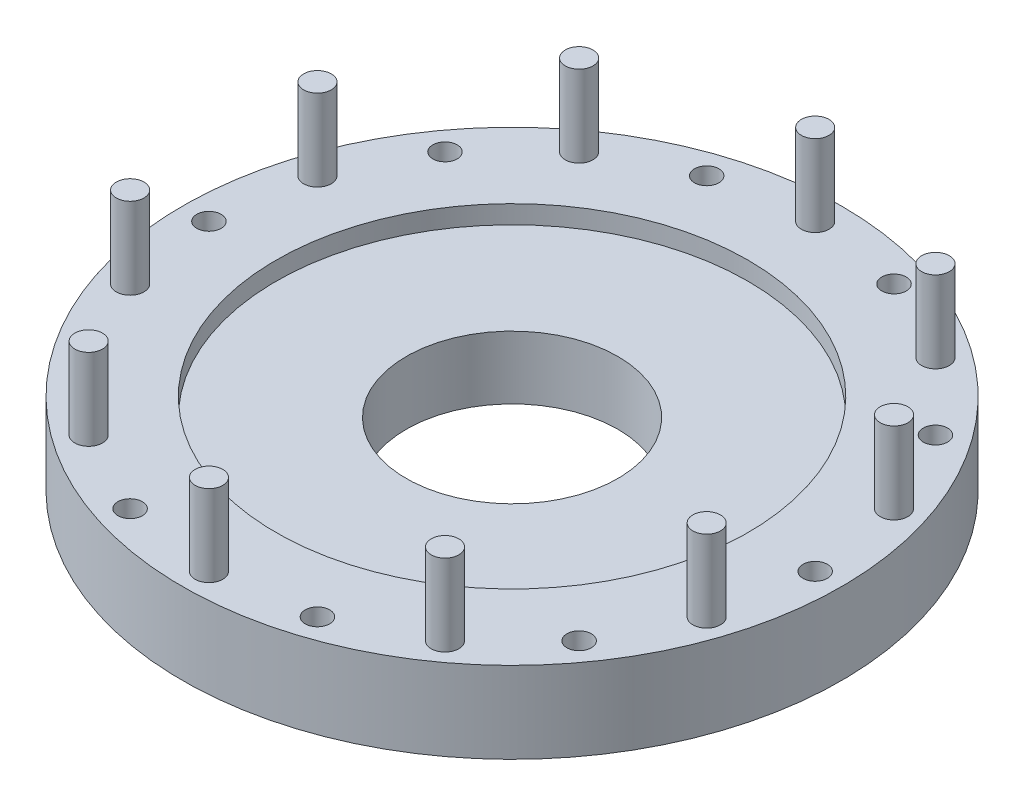
SolidWorks part; units mm, degrees
material "ABS"
ref_plane "Front Plane" through (0, 0, 0) normal (0, 0, 1) x (1, 0, 0)
ref_plane "Top Plane" through (0, 0, 0) normal (0, 1, 0) x (1, 0, 0)
ref_plane "Right Plane" through (0, 0, 0) normal (1, 0, 0) x (0, 0, -1)
sketch "Sketch1" plane through (0, 0, 0) normal (0, 0, 1) x (1, 0, 0)
  line L0 (0, -1.7519) -> (0, 48.3018) construction
  line L1 (-29, 10) -> (-40.5, 10)
  line L4 (-40.5, 10) -> (-40.5, 0)
  line L5 (-40.5, 0) -> (-13, 0)
  line L6 (-13, 0) -> (-13, 7.75)
  line L7 (-13, 7.75) -> (-29, 7.75)
  line L8 (-29, 7.75) -> (-29, 10)
  dimension "D1" = 40.5
  dimension "D3" = 2.25
  dimension "D2" = 29
  dimension "D4" = 13
  dimension "D5" = 10
revolve "Revolve1" add sketch "Sketch1" angle 360 about L0
sketch "Sketch2" plane through (0, 10, 0) normal (0, 1, 0) x (1, 0, 0)
  line L0 (0, 37.25) -> (0, 0) construction
  line L1 (0, 0) -> (11.5109, 35.4269) construction
  circle A0 centre (0, 0) radius 37.25 construction
  circle A1 centre (0, 37.25) radius 1.7
  circle A2 centre (11.5109, 35.4269) radius 1.5
  circle A3 centre (21.895, 30.1359) radius 1.7
  circle A4 centre (30.1359, 21.895) radius 1.5
  circle A5 centre (35.4269, 11.5109) radius 1.7
  circle A6 centre (37.25, 0) radius 1.5
  circle A7 centre (35.4269, -11.5109) radius 1.7
  circle A8 centre (30.1359, -21.895) radius 1.5
  circle A9 centre (21.895, -30.1359) radius 1.7
  circle A10 centre (11.5109, -35.4269) radius 1.5
  circle A11 centre (0, -37.25) radius 1.7
  circle A12 centre (-11.5109, -35.4269) radius 1.5
  circle A13 centre (-21.895, -30.1359) radius 1.7
  circle A14 centre (-30.1359, -21.895) radius 1.5
  circle A15 centre (-35.4269, -11.5109) radius 1.7
  circle A16 centre (-37.25, 0) radius 1.5
  circle A17 centre (-35.4269, 11.5109) radius 1.7
  circle A18 centre (-30.1359, 21.895) radius 1.5
  circle A19 centre (-21.895, 30.1359) radius 1.7
  circle A20 centre (-11.5109, 35.4269) radius 1.5
  point P37 (0, 0)
  dimension "D5" = 10
  dimension "D1" = 74.5
  dimension "D2" = 3.4
  dimension "D3" = 3
  dimension "D4" = 18
extrude "Cut-Extrude1" cut sketch "Sketch2" against normal through all both and the other way through all
sketch "Sketch3" plane through (0, 0, 0) normal (0, 0, 1) x (1, 0, 0)
  line L0 (28.5, 4) -> (28.5, 0)
  line L2 (28.5, 0) -> (21.5, 0)
  line L3 (21.5, 0) -> (21.5, 4)
  line L6 (25, 4) -> (25, 0) construction
  line L7 (0, -19.0654) -> (0, 22.7714) construction
  line L8 (-40.5, 0) -> (40.5, 0) construction
  line L9 (28.5, 4) -> (21.5, 4)
  dimension "D1" = 25
  dimension "D2" = 4
  dimension "D3" = 7
revolve "Cut-Revolve1" cut sketch "Sketch3" angle 360 about L7
sketch "Sketch4" plane through (0, 0, 0) normal (0, -1, 0) x (1, 0, 0)
  line L0 (10.8507, 38.5329) -> (8.4909, 36.4081)
  line L1 (8.4909, 36.4081) -> (9.1511, 33.3021)
  line L2 (9.1511, 33.3021) -> (12.1711, 32.3208)
  line L3 (12.1711, 32.3208) -> (14.5309, 34.4456)
  line L4 (14.5309, 34.4456) -> (13.8707, 37.5516)
  line L5 (13.8707, 37.5516) -> (10.8507, 38.5329)
  line L6 (13.8707, 37.5516) -> (9.1511, 33.3021) construction
  line L49 (33.2939, 22.2269) -> (31.4274, 24.7959)
  line L50 (12.3607, 38.0423) -> (12.5152, 38.5178) construction
  line L51 (16.0251, 37.3773) -> (16.3077, 37.2855) construction
  line L52 (31.4274, 24.7959) -> (28.2694, 24.464)
  line L53 (28.2694, 24.464) -> (26.9779, 21.5631)
  line L54 (26.9779, 21.5631) -> (28.8443, 18.9941)
  line L55 (28.8443, 18.9941) -> (32.0024, 19.326)
  line L56 (32.0024, 19.326) -> (33.2939, 22.2269)
  line L57 (40, -1.5877) -> (40, 1.5877)
  line L58 (40, 1.5877) -> (37.25, 3.1754)
  line L59 (37.25, 3.1754) -> (34.5, 1.5877)
  line L60 (34.5, 1.5877) -> (34.5, -1.5877)
  line L61 (34.5, -1.5877) -> (37.25, -3.1754)
  line L62 (37.25, -3.1754) -> (40, -1.5877)
  line L63 (31.4274, -24.7959) -> (33.2939, -22.2269)
  line L64 (33.2939, -22.2269) -> (32.0024, -19.326)
  line L65 (32.0024, -19.326) -> (28.8443, -18.9941)
  line L66 (28.8443, -18.9941) -> (26.9779, -21.5631)
  line L67 (26.9779, -21.5631) -> (28.2694, -24.464)
  line L68 (28.2694, -24.464) -> (31.4274, -24.7959)
  line L69 (10.8507, -38.5329) -> (13.8707, -37.5516)
  line L70 (13.8707, -37.5516) -> (14.5309, -34.4456)
  line L71 (14.5309, -34.4456) -> (12.1711, -32.3208)
  line L72 (12.1711, -32.3208) -> (9.1511, -33.3021)
  line L73 (9.1511, -33.3021) -> (8.4909, -36.4081)
  line L74 (8.4909, -36.4081) -> (10.8507, -38.5329)
  line L75 (-13.8707, -37.5516) -> (-10.8507, -38.5329)
  line L76 (-10.8507, -38.5329) -> (-8.4909, -36.4081)
  line L77 (-8.4909, -36.4081) -> (-9.1511, -33.3021)
  line L78 (-9.1511, -33.3021) -> (-12.1711, -32.3208)
  line L79 (-12.1711, -32.3208) -> (-14.5309, -34.4456)
  line L80 (-14.5309, -34.4456) -> (-13.8707, -37.5516)
  line L81 (-33.2939, -22.2269) -> (-31.4274, -24.7959)
  line L82 (-31.4274, -24.7959) -> (-28.2694, -24.464)
  line L83 (-28.2694, -24.464) -> (-26.9779, -21.5631)
  line L84 (-26.9779, -21.5631) -> (-28.8443, -18.9941)
  line L85 (-28.8443, -18.9941) -> (-32.0024, -19.326)
  line L86 (-32.0024, -19.326) -> (-33.2939, -22.2269)
  line L87 (-40, 1.5877) -> (-40, -1.5877)
  line L88 (-40, -1.5877) -> (-37.25, -3.1754)
  line L89 (-37.25, -3.1754) -> (-34.5, -1.5877)
  line L90 (-34.5, -1.5877) -> (-34.5, 1.5877)
  line L91 (-34.5, 1.5877) -> (-37.25, 3.1754)
  line L92 (-37.25, 3.1754) -> (-40, 1.5877)
  line L93 (-31.4274, 24.7959) -> (-33.2939, 22.2269)
  line L94 (-33.2939, 22.2269) -> (-32.0024, 19.326)
  line L95 (-32.0024, 19.326) -> (-28.8443, 18.9941)
  line L96 (-28.8443, 18.9941) -> (-26.9779, 21.5631)
  line L97 (-26.9779, 21.5631) -> (-28.2694, 24.464)
  line L98 (-28.2694, 24.464) -> (-31.4274, 24.7959)
  line L99 (-10.8507, 38.5329) -> (-13.8707, 37.5516)
  line L100 (-13.8707, 37.5516) -> (-14.5309, 34.4456)
  line L101 (-14.5309, 34.4456) -> (-12.1711, 32.3208)
  line L102 (-12.1711, 32.3208) -> (-9.1511, 33.3021)
  line L103 (-9.1511, 33.3021) -> (-8.4909, 36.4081)
  line L104 (-8.4909, 36.4081) -> (-10.8507, 38.5329)
  line L105 (0, 0) -> (12.1711, 32.3208) construction
  line L106 (0, 0) -> (28.8443, 18.9941) construction
  line L107 (28.8443, 18.9941) -> (31.4274, 24.7959) construction
  circle A1 centre (21.895, 30.1359) radius 1.7 construction
  circle A2 centre (21.895, 30.1359) radius 1.7 construction
  circle A4 centre (11.5109, 35.4269) radius 1.5 construction
  circle A5 centre (11.5109, 35.4269) radius 1.5 construction
  circle A7 centre (0, 0) radius 40.5 construction
  circle A9 centre (30.1359, 21.895) radius 1.5 construction
  circle A10 centre (30.1359, 21.895) radius 1.5 construction
  point P57 (4.489, 6.1786)
  dimension "D1" = 120
  dimension "D2" = 120
  dimension "D3" = 5.5
  dimension "D4" = 10
  dimension "D5" = 36
extrude "Cut-Extrude2" cut sketch "Sketch4" against normal blind 5
sketch "Sketch5" plane through (0, 0, 0) normal (0, -1, 0) x (1, 0, 0)
  circle A0 centre (21.895, 30.1359) radius 1.7 construction
  circle A1 centre (21.895, 30.1359) radius 1.7
  circle A2 centre (35.4269, 11.5109) radius 1.7 construction
  circle A3 centre (35.4269, -11.5109) radius 1.7 construction
  circle A4 centre (21.895, -30.1359) radius 1.7 construction
  circle A5 centre (0, -37.25) radius 1.7 construction
  circle A6 centre (-35.4269, 11.5109) radius 1.7 construction
  circle A7 centre (-21.895, 30.1359) radius 1.7 construction
  circle A8 centre (0, 37.25) radius 1.7 construction
  circle A9 centre (35.4269, 11.5109) radius 1.7
  circle A10 centre (35.4269, -11.5109) radius 1.7
  circle A11 centre (21.895, -30.1359) radius 1.7
  circle A12 centre (0, -37.25) radius 1.7
  circle A13 centre (-35.4269, 11.5109) radius 1.7
  circle A14 centre (-21.895, 30.1359) radius 1.7
  circle A15 centre (0, 37.25) radius 1.7
  circle A16 centre (-21.895, -30.1359) radius 1.7 construction
  circle A17 centre (-35.4269, -11.5109) radius 1.7 construction
  circle A18 centre (-21.895, -30.1359) radius 1.7
  circle A19 centre (-35.4269, -11.5109) radius 1.7
extrude "Boss-Extrude1" add sketch "Sketch5" against normal blind 20
equation "\"Stator_OD\"= 60'No Tolerance given"
equation "\"A\"=35.81 'taken off spec sheet for 06808 (A)"
equation "\"Rotor_ID\"= 30'No Tolerance Given"
equation "\"back_bearing_Thickness\"= 5'-0.12"
equation "\"back_bearing_OD\"= 24'-0.009 https://www.mcmaster.com/5972K155/"
equation "\"Stator_Gap\"= 0.0375'+- 0.0125 (From 1.3.3.1 Kollmorgen manual)"
equation "\"Back_mount_hole\"= 1.75'To be tapped to M2 (USE LOCKTITE)"
equation "\"facePlate_Mount_Hole\"= 2.75'To be tapped to M3"
equation "\"final_shaftD\"= 12'To fit in harmonic"
equation "\"final_shaftL\"= 5.25+3+\"sheet_thick\"+\"connector_thick\"-3+\"harmon_coupleL\"+0.5-\"shaft_Ladjust\"'length to make everything nice and aligned"
equation "\"back_bearing_ID\"= 15'"
equation "\"back_bearing_IDOD\"= 16.5'measured off CAD, actually 16.75, but rounded down to nicer number"
equation "\"rotor_shaftD\"= \"Rotor_ID\" - (\"rotor-shaft_gap\")*2'"
equation "\"front_bearing_ID\"= 12'https://www.mcmaster.com/5972K154/"
equation "\"front_bearing_OD\"= 21'-0.009"
equation "\"front_bearing_IDOD\"= 13.5'Measured off CAD. Actually 13.75, but rounded down"
equation "\"rotor-shaft_gap\" = 0.0185 '+-0.0065 (from manual)"
equation "\"front_bearing_Thickness\"= 5'-0.12"
equation "\"rotor_thickness\"= 2.4'measured off CAD"
equation "\"rotor_height\"= 32.86'+-0.075 taken off spec sheet for 06826 (C)"
equation "\"B\"= 26.3'+-0.35 taken off spec sheet for 06826"
equation "\"key_L\"= 20'-0.2 https://www.mcmaster.com/2977N19/"
equation "\"key_H\"= 4'-0.03"
equation "\"key_W\"= 4'-0.03"
equation "\"harmon_keyH\"= 13.8'+0.1 from drawing"
equation "\"harmon_coupleL\"= 21.5' taken from drawing https://www.harmonicdrive.net/_hd/content/caddownloads/dxf/csf-2uh-ulw_gearheads/CSF-17-xxx-2UH-ULW.pdf"
equation "\"harmon_diam\"= 81' from drawing"
equation "\"harmon_BCD\"= 74.5' from drawing"
equation "\"harmon_holeD1\"= 3.4' from drawing"
equation "\"harmon_holeD2\"= 3' from drawing"
equation "\"harmon_holeAng\"= 18' from drawing"
equation "\"sheet_thick\"= 1/8*25.4 'random, replace w actual sheet thickness when u feel like :)"
equation "\"D1@Sketch1\"=\"harmon_diam\"/2"
equation "\"D1@Sketch2\"=\"harmon_BCD\""
equation "\"D2@Sketch2\"=\"harmon_holeD1\""
equation "\"D3@Sketch2\"=\"harmon_holeD2\""
equation "\"D4@Sketch2\"=\"harmon_holeAng\""
equation "\"nut-thickness\"= 5 'idk measure the ones in the shop and adjust"
equation "\"D1@Cut-Extrude2\"=\"nut-thickness\""
equation "\"connector_thick\"= 10' random for now"
equation "\"D5@Sketch1\"=\"connector_thick\""
equation "\"shaft_Ladjust\"= 6.75' sorry. It's silly, but it works."
equation "\"D1@Boss-Extrude1\"=\"connector_thick\"+10"
